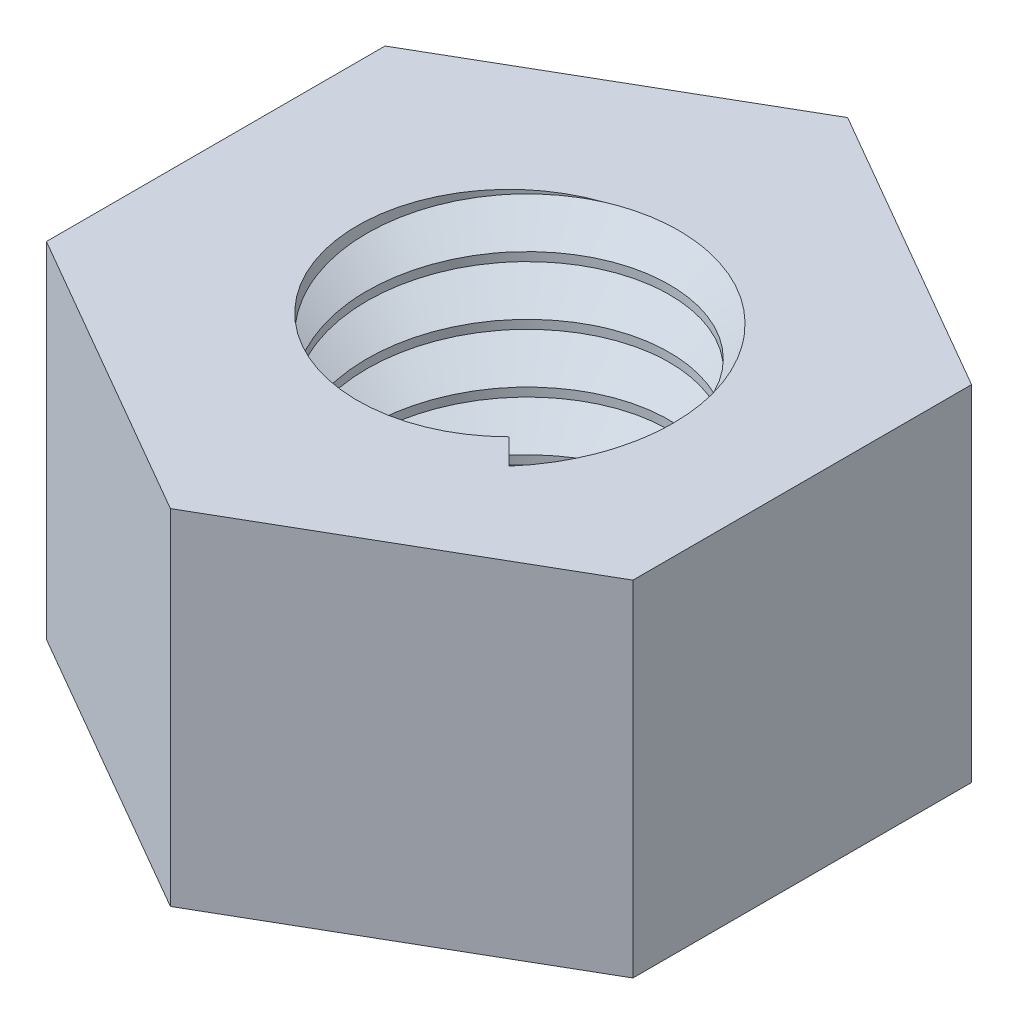
SolidWorks part; units mm, degrees
material "Acero aleado"
ref_plane "Alzado" through (0, 0, 0) normal (0, 0, 1) x (1, 0, 0)
ref_plane "Planta" through (0, 0, 0) normal (0, 1, 0) x (1, 0, 0)
ref_plane "Vista lateral" through (0, 0, 0) normal (1, 0, 0) x (0, 0, -1)
sketch "Sk_Hexagono" plane through (0, 0, 0) normal (0, 1, 0) x (1, 0, 0)
  line L0 (4, -2.3094) -> (0, -4.6188)
  line L1 (0, -4.6188) -> (-4, -2.3094)
  line L2 (-4, -2.3094) -> (-4, 2.3094)
  line L3 (-4, 2.3094) -> (0, 4.6188)
  line L4 (0, 4.6188) -> (4, 2.3094)
  line L5 (4, 2.3094) -> (4, -2.3094)
extrude "Hexagono" add sketch "Sk_Hexagono" along normal blind 4.7 from offset 0
sketch3d "Sk_Taladro"
  line L0 (0, -1, 0) -> (0, 5.7, 0)
  dimension "D1" = 6.7
sweep "Taladro" cut path "Sk_Taladro" circular profile diameter 4.134 parameters "D3"=4.134
sketch "Sk_Helice" plane through (0, 0, 0) normal (0, 1, 0) x (1, 0, 0)
  circle A0 centre (0, 0) radius 2.067
curve "Helice_rosca" pitch 0.8 height 4.7 turns 5.875
sketch "Sk_Perfil_rosca" plane through (0, 0, 0) normal (1, 0, 0) x (0, 0, -1)
  line L0 (-1.867, -0.48) -> (-2.5577, 0)
  line L1 (-2.5577, 0) -> (-1.867, 0.48)
  line L2 (-1.867, 0.48) -> (-1.867, -0.48)
sweep "Rosca_M5x0,8" cut profiles "Sk_Perfil_rosca" path "Helice_rosca"
